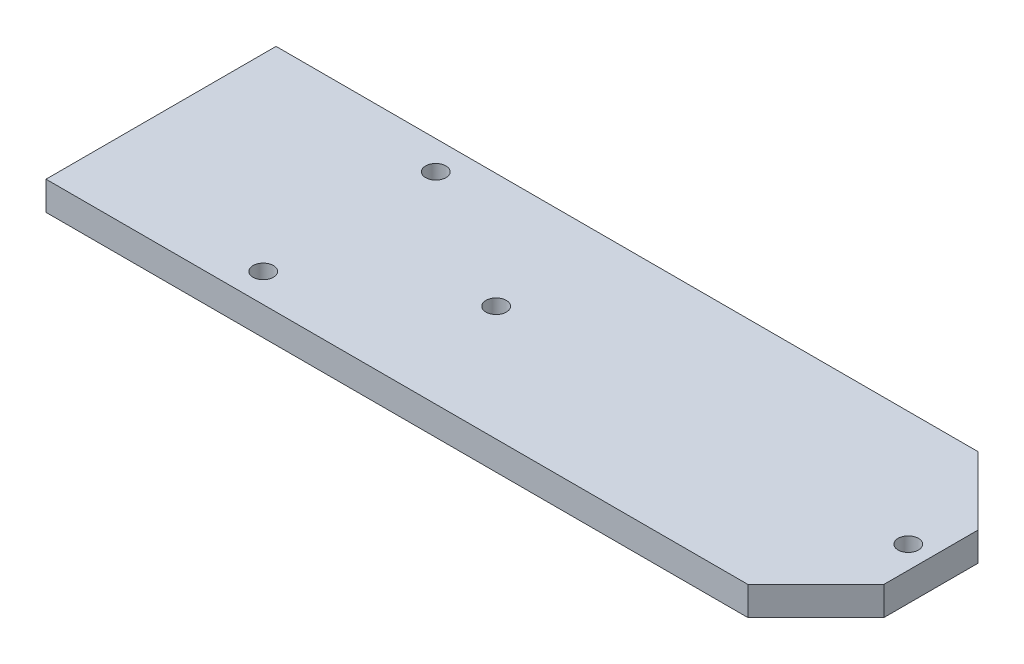
SolidWorks part; units mm, degrees
ref_plane "Front Plane" through (0, 0, 0) normal (0, 0, 1) x (1, 0, 0)
ref_plane "Top Plane" through (0, 0, 0) normal (0, 1, 0) x (1, 0, 0)
ref_plane "Right Plane" through (0, 0, 0) normal (1, 0, 0) x (0, 0, -1)
sketch "Sketch1" plane through (0, 0, 0) normal (0, 1, 0) x (1, 0, 0)
  line L1 (0, 0) -> (170, 0)
  line L2 (0, 0) -> (0, 50.8)
  line L3 (0, 50.8) -> (170, 50.8)
  line L4 (170, 0) -> (170, 50.8)
  circle A0 centre (165, 25.4) radius 2.25
  circle A1 centre (74, 25.4) radius 2.25
  circle A2 centre (41.619, 44.45) radius 2.25
  circle A3 centre (41.619, 6.35) radius 2.25
  dimension "D1" = 5
  dimension "D2" = 91
  dimension "D6" = 38.1
  dimension "D3" = 170
  dimension "D4" = 50.8
  dimension "D5" = 25.4
  dimension "D7" = 6.35
  dimension "D8" = 41.619
extrude "Boss-Extrude1" add sketch "Sketch1" along normal blind 6.35 contours L3 L4 L1 L2
chamfer "Chamfer1" distance 15 angle 45 2 edges at (170, 3.175, 0) (170, 3.175, -50.8)
sketch "Sketch2" plane through (0, 0, 0) normal (-1, 0, 0) x (0, 0, 1)
  line L0 (-50.8, 6.35) -> (0, 6.35) construction
  line L1 (-50.8, 6.35) -> (-50.8, 0) construction
  circle A0 centre (-7.9, 3.175) radius 1.75
  circle A1 centre (-42.9, 3.175) radius 1.75
  dimension "D1" = 7.9
  dimension "D2" = 35
  dimension "D3" = 3.175
  dimension "D4" = 3.175
hole_wizard "M4x0.7 Tapped Hole1" positions "Sketch4" profile "Sketch3" tap size "M4x0.7" standard "ANSI Metric"
sketch "Sketch4" plane through (0, 0, 0) normal (-1, 0, 0) x (0, 0, 1)
  point P0 (-42.9, 3.175)
  point P3 (-7.9, 3.175)
sketch "Sketch3" plane through (0, 3.175, -42.9) normal (0, 1, 0) x (0, 0, 1)
  line L0 (0, 0) -> (0, 26.3914)
  line L1 (0, 26.3914) -> (1.65, 25.4)
  line L2 (1.65, 25.4) -> (1.65, 0)
  line L5 (1.65, 0) -> (0, 0)
  line L10 (0, 26.3914) -> (-1.65, 25.4) construction
  line L11 (0, -6.35) -> (0, 107.95) construction
  dimension "Tap Drill Dia." = 3.3
  dimension "Tap Drill Depth" = 25.4
  dimension "Drill Angle" = 118
cosmetic thread "Hole Thread1" parameters "D1"=20, "D2"=4
cosmetic thread "Hole Thread2" parameters "D1"=20, "D2"=4
